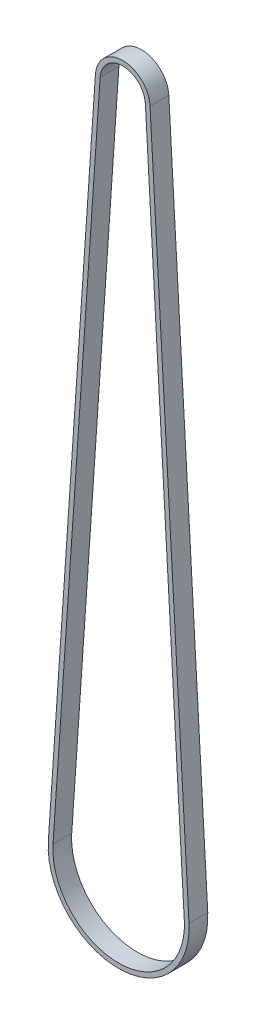
SolidWorks part; units mm, degrees
ref_plane "前视基准面" through (0, 0, 0) normal (0, 0, 1) x (1, 0, 0)
ref_plane "上视基准面" through (0, 0, 0) normal (0, 1, 0) x (1, 0, 0)
ref_plane "右视基准面" through (0, 0, 0) normal (1, 0, 0) x (0, 0, -1)
other "Configuration Table"
sketch "草图2" plane through (0, 0, 0) normal (0, 0, 1) x (1, 0, 0)
  line L0 (0, 0) -> (1, 0) construction
  line L1 (0, 0) -> (0, 1) construction
  line L2 (7.2384, 0.4097) -> (19.7007, -219.7466)
  line L3 (-22.3163, -219.4964) -> (-7.233, 0.4959)
  arc A0 (-7.233, 0.4959) -> (7.2384, 0.4097) centre (0, 0) cw
  arc A1 (19.7007, -219.7466) -> (-22.3163, -219.4964) centre (-1.3156, -220.9363) cw
extrude "拉伸-薄壁1" add sketch "草图2" along normal blind 6 thin thin type one direction wall 1.5
